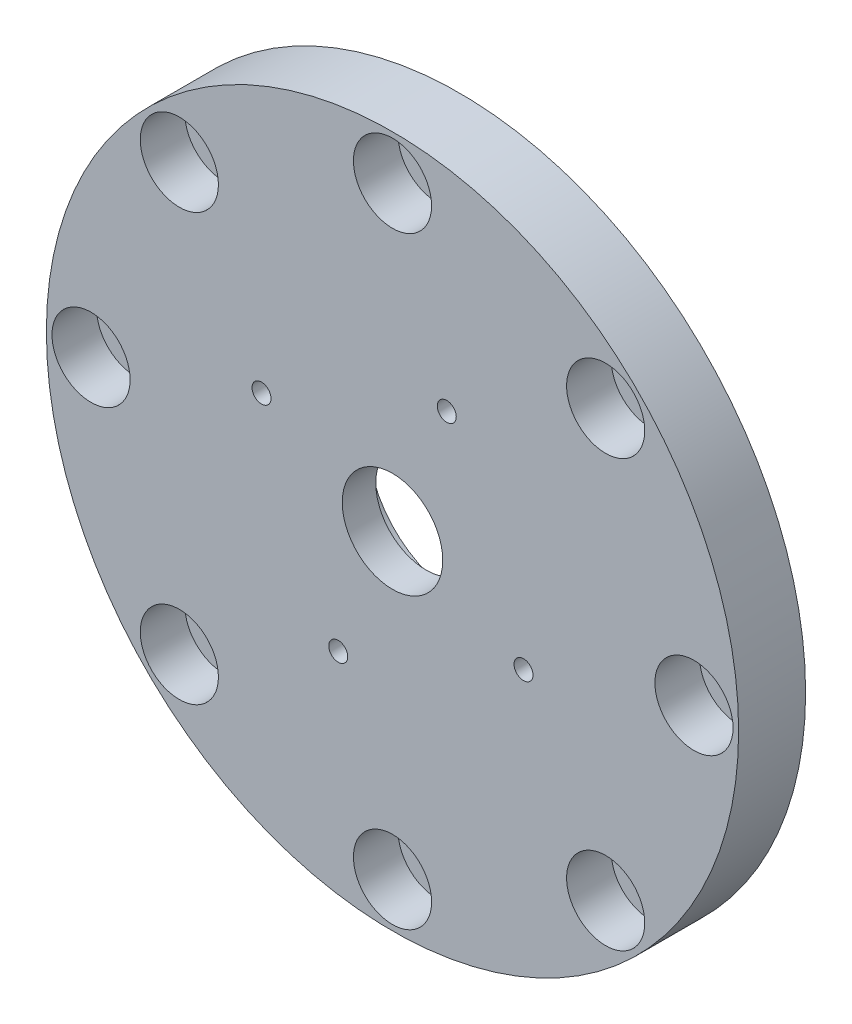
SolidWorks part; units mm, degrees
ref_plane "Front Plane" through (0, 0, 0) normal (0, 0, 1) x (1, 0, 0)
ref_plane "Top Plane" through (0, 0, 0) normal (0, 1, 0) x (1, 0, 0)
ref_plane "Right Plane" through (0, 0, 0) normal (1, 0, 0) x (0, 0, -1)
sketch "Sketch1" plane through (0, 0, 0) normal (0, 0, 1) x (1, 0, 0)
  line L11 (0, 0) -> (4.8601, 11.7333) construction
  line L14 (-11.7333, 4.8601) -> (11.7333, -4.8601) construction
  line L17 (0, 0) -> (-27, 0) construction
  circle A2 centre (0, 0) radius 4.5
  circle A3 centre (0, 0) radius 12.7 construction
  circle A11 centre (4.8601, 11.7333) radius 0.85
  circle A12 centre (11.7333, -4.8601) radius 0.85
  circle A13 centre (-4.8601, -11.7333) radius 0.85
  circle A14 centre (-11.7333, 4.8601) radius 0.85
  circle A33 centre (0, 0) radius 24 construction
  circle A34 centre (0, 0) radius 31
  circle A35 centre (-27, 0) radius 1.55
  circle A36 centre (-19.0919, 19.0919) radius 1.55
  circle A37 centre (0, 27) radius 1.55
  circle A38 centre (19.0919, 19.0919) radius 1.55
  circle A39 centre (27, 0) radius 1.55
  circle A40 centre (19.0919, -19.0919) radius 1.55
  circle A41 centre (0, -27) radius 1.55
  circle A42 centre (-19.0919, -19.0919) radius 1.55
  point P7 (0, 0)
  point P10 (0, 0)
  point P12 (0, 0)
  point P16 (0, 0)
  point P17 (0, 0)
  point P20 (0, 0)
  point P30 (0, 0)
  point P39 (0, 0)
  point P40 (0, 0)
  point P47 (0, 0)
  point P64 (0, 0)
  dimension "D1" = 4
extrude "Boss-Extrude2" add sketch "Sketch1" along normal blind 6
sketch "Sketch5" plane through (0, 0, 0) normal (0, 0, -1) x (-1, 0, 0)
  circle A0 centre (0, 0) radius 8.2
extrude "Cut-Extrude3" cut sketch "Sketch5" against normal blind 3
sketch "Sketch6" plane through (0, 0, 6) normal (0, 0, 1) x (1, 0, 0)
  circle A7 centre (0, 27) radius 3.5
  circle A8 centre (19.0919, 19.0919) radius 3.5
  circle A9 centre (27, 0) radius 3.5
  circle A10 centre (19.0919, -19.0919) radius 3.5
  circle A11 centre (0, -27) radius 3.5
  circle A12 centre (-19.0919, -19.0919) radius 3.5
  circle A13 centre (-27, 0) radius 3.5
  circle A14 centre (-19.0919, 19.0919) radius 3.5
  point P11 (-3.75, 3.75)
  point P29 (0, 0)
  point P31 (0, 0)
  dimension "D2" = 8
extrude "Cut-Extrude4" cut sketch "Sketch6" against normal blind 4
sketch "Sketch7" plane through (0, 0, 0) normal (0, 0, -1) x (-1, 0, 0)
  circle A1 centre (-4.8601, 11.7333) radius 2.2
  circle A2 centre (11.7333, 4.8601) radius 2.2
  circle A3 centre (4.8601, -11.7333) radius 2.2
  circle A4 centre (-11.7333, -4.8601) radius 2.2
  point P2 (0, 0)
  point P12 (0, 0)
  dimension "D1" = 4
extrude "Cut-Extrude5" cut sketch "Sketch7" against normal blind 2
